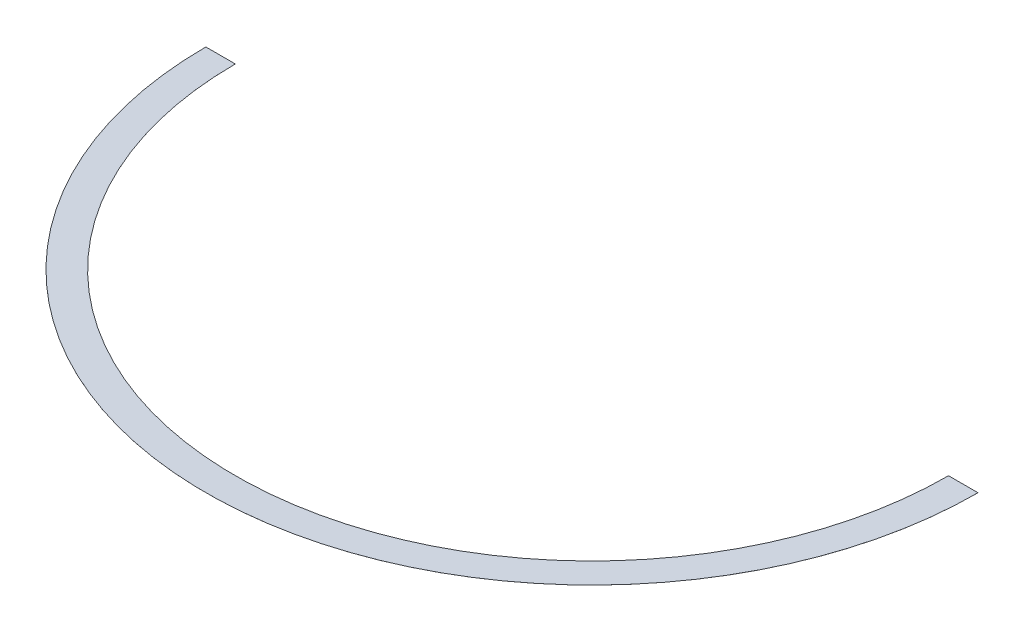
SolidWorks part; units mm, degrees
ref_plane "Plano frontal" through (0, 0, 0) normal (0, 0, 1) x (1, 0, 0)
ref_plane "Plano superior" through (0, 0, 0) normal (0, 1, 0) x (1, 0, 0)
ref_plane "Plano direito" through (0, 0, 0) normal (1, 0, 0) x (0, 0, -1)
sketch "Esboço1" plane through (0, 0, 0) normal (0, 1, 0) x (1, 0, 0)
  line L0 (-1093, 595.536) -> (-1073, 595.536)
  line L1 (0, 0) -> (18.9344, 0)
  line L2 (0, 0) -> (0, 766.8662)
  line L3 (0, 766.8662) -> (18.9344, 766.8662)
  line L4 (18.9344, 0) -> (18.9344, 766.8662)
  line L5 (-381.6968, 766.8662) -> (-362.7624, 766.8662)
  line L6 (-381.6968, 766.8662) -> (-381.6968, 345.536)
  line L7 (-381.6968, 345.536) -> (-362.7624, 345.536)
  line L8 (-362.7624, 766.8662) -> (-362.7624, 345.536)
  line L9 (-858.9344, 645.536) -> (-840, 645.536)
  line L10 (-858.9344, 645.536) -> (-858.9344, 345.536)
  line L11 (-858.9344, 345.536) -> (-840, 345.536)
  line L12 (-840, 645.536) -> (-840, 345.536)
  line L13 (-853.5858, 925.2213) -> (-1253.5858, 925.2213)
  line L14 (-853.5858, 925.2213) -> (-853.5858, 945.2213)
  line L15 (-853.5858, 945.2213) -> (-1253.5858, 945.2213)
  line L16 (-1253.5858, 925.2213) -> (-1253.5858, 945.2213)
  line L17 (-1093, 595.536) -> (-1093, 195.536)
  line L18 (-1093, 195.536) -> (-1073, 195.536)
  line L19 (-1073, 595.536) -> (-1073, 195.536)
  line L21 (-858.9344, 427.7897) -> (-1250.0103, 427.7897)
  line L23 (-858.9344, 407.7897) -> (-1250.0103, 407.7897)
  line L24 (-1250.0103, 427.7897) -> (-1250.0103, 407.7897)
  line L33 (-1439.6613, 239.7512) -> (-1560.0448, 239.7512)
  line L34 (-1439.6613, 239.7512) -> (-1439.6613, 219.7512)
  line L35 (-1439.6613, 219.7512) -> (-1560.0448, 219.7512)
  line L36 (-1560.0448, 239.7512) -> (-1560.0448, 219.7512)
  line L37 (-1627.2015, 576.144) -> (-1607.2015, 576.144)
  line L38 (-1627.2015, 576.144) -> (-1627.2015, 317.0654)
  line L39 (-1627.2015, 317.0654) -> (-1607.2015, 317.0654)
  line L40 (-1607.2015, 576.144) -> (-1607.2015, 317.0654)
  line L41 (-1627.2015, 769.6927) -> (-1607.2015, 769.6927)
  line L42 (-1627.2015, 769.6927) -> (-1627.2015, 1019.6927)
  line L43 (-1627.2015, 1019.6927) -> (-1607.2015, 1019.6927)
  line L44 (-1607.2015, 769.6927) -> (-1607.2015, 1019.6927)
  line L59 (637.1559, 1114.7605) -> (656.0903, 1114.7605)
  line L60 (159.9183, 1114.7605) -> (178.8527, 1114.7605)
  arc A6 (-381.6968, 766.8662) -> (18.9344, 766.8662) centre (-181.3812, 766.8662) cw
  arc A7 (-362.7624, 766.8662) -> (0, 766.8662) centre (-181.3812, 766.8662) cw
  arc A8 (-362.7624, 345.536) -> (-858.9344, 345.536) centre (-610.8484, 345.536) cw
  arc A9 (-381.6968, 345.536) -> (-840, 345.536) centre (-610.8484, 345.536) cw
  arc A10 (-840, 645.536) -> (-803.6955, 702.0415) centre (-777.8744, 645.536) cw
  arc A11 (-803.6955, 702.0415) -> (-853.5858, 945.2213) centre (-856.6336, 817.8884) ccw
  arc A12 (-858.9344, 645.536) -> (-814.4955, 717.9247) centre (-777.7563, 645.536) cw
  arc A13 (-814.4955, 717.9247) -> (-853.5858, 925.2213) centre (-864.2122, 815.8835) ccw
  arc A14 (-1093, 595.536) -> (-1188.5366, 677.9223) centre (-1176.2913, 595.536) ccw
  arc A15 (-1188.5366, 677.9223) -> (-1354.3411, 742.8189) centre (-1214.8489, 854.9525) cw
  arc A16 (-1354.3411, 742.8189) -> (-1253.5858, 945.2213) centre (-1257.3278, 820.805) cw
  arc A17 (-1073, 595.536) -> (-1188.5366, 698.0004) centre (-1176.2038, 595.536) ccw
  arc A18 (-1188.5366, 698.0004) -> (-1341.8208, 766.8662) centre (-1207.9995, 859.705) cw
  arc A19 (-1341.8208, 766.8662) -> (-1253.5858, 925.2213) centre (-1258.876, 824.4093) cw
  arc A22 (-1368.7558, 309.7722) -> (-1439.6613, 219.7512) centre (-1474.849, 320.402) cw
  arc A23 (-1388.5562, 309.7722) -> (-1439.6613, 239.7512) centre (-1477.6183, 321.1143) cw
  arc A24 (-1388.5562, 309.7722) -> (-1250.0103, 427.7897) centre (-1254.4723, 292.6965) cw
  arc A25 (-1607.2015, 317.0654) -> (-1560.0448, 239.7512) centre (-1520.2441, 317.0654) ccw
  arc A26 (-1627.2015, 317.0654) -> (-1560.0448, 219.7512) centre (-1523.1159, 317.0654) ccw
  arc A27 (-1368.7558, 309.7722) -> (-1250.0103, 407.7897) centre (-1259.9289, 298.8686) cw
  arc A30 (656.0903, 1114.7605) -> (159.9183, 1114.7605) centre (408.0043, 1114.7605) cw
  arc A31 (637.1559, 1114.7605) -> (178.8527, 1114.7605) centre (408.0043, 1114.7605) cw
extrude "Ressalto-extrusão8" add sketch "Esboço1" along normal blind 0.01 contours A30 L60 A31 L59
